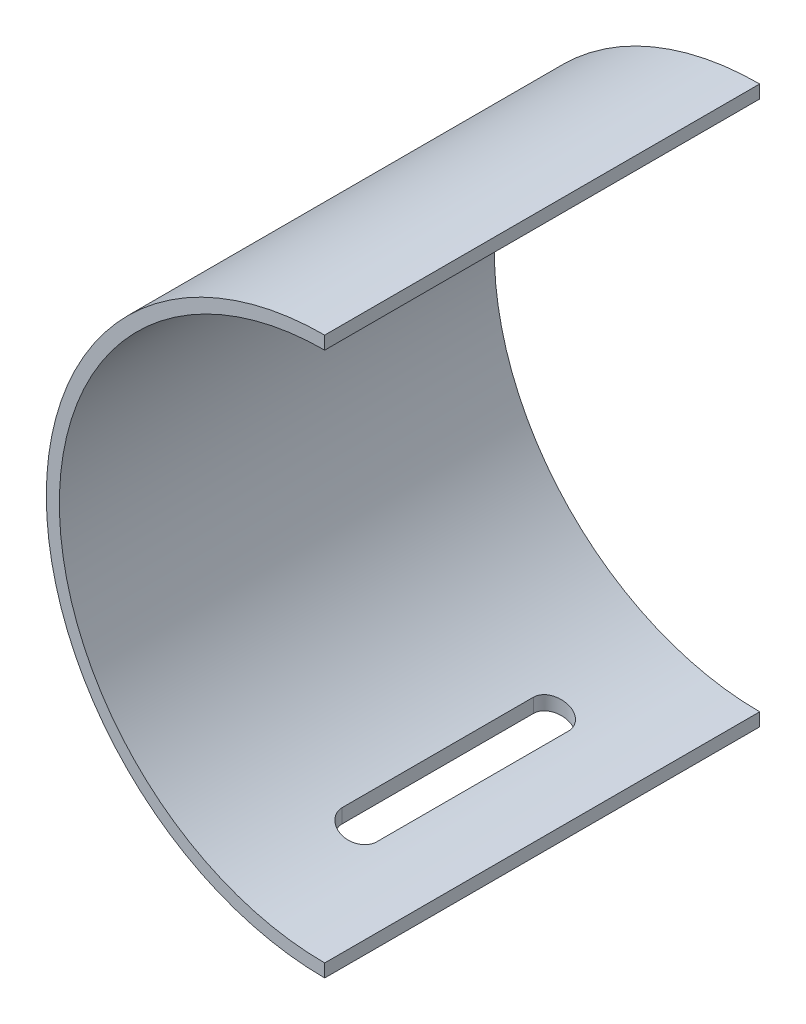
SolidWorks part; units mm, degrees
ref_plane "Alzado" through (0, 0, 0) normal (0, 0, 1) x (1, 0, 0)
ref_plane "Planta" through (0, 0, 0) normal (0, 1, 0) x (1, 0, 0)
ref_plane "Vista lateral" through (0, 0, 0) normal (1, 0, 0) x (0, 0, -1)
sketch "Croquis1" plane through (0, 0, 0) normal (0, 0, 1) x (1, 0, 0)
  line L0 (0, 16) -> (0, 15.25)
  line L1 (0, -15.25) -> (0, -16)
  arc A0 (0, 16) -> (0, -16) centre (0, 0) ccw
  arc A1 (0, 15.25) -> (0, -15.25) centre (0, 0) ccw
  dimension "D1" = 32
  dimension "D2" = 30.5
extrude "Saliente-Extruir1" add sketch "Croquis1" along normal blind 25
sketch "Croquis2" plane through (0, 0, 0) normal (0, 1, 0) x (1, 0, 0)
  line L0 (-5, -7) -> (-5, -18) construction
  line L1 (-4, -7) -> (-4, -18)
  line L2 (-6, -7) -> (-6, -18)
  line L3 (0, -25) -> (0, 0) construction
  arc A0 (-4, -7) -> (-6, -7) centre (-5, -7) ccw
  arc A1 (-6, -18) -> (-4, -18) centre (-5, -18) ccw
  point P2 (-5, -12.5)
  point P10 (0, -12.5)
  dimension "D2" = 11
  dimension "D1" = 2
  dimension "D3" = 4
extrude "Cortar-Extruir1" cut sketch "Croquis2" against normal blind 25
